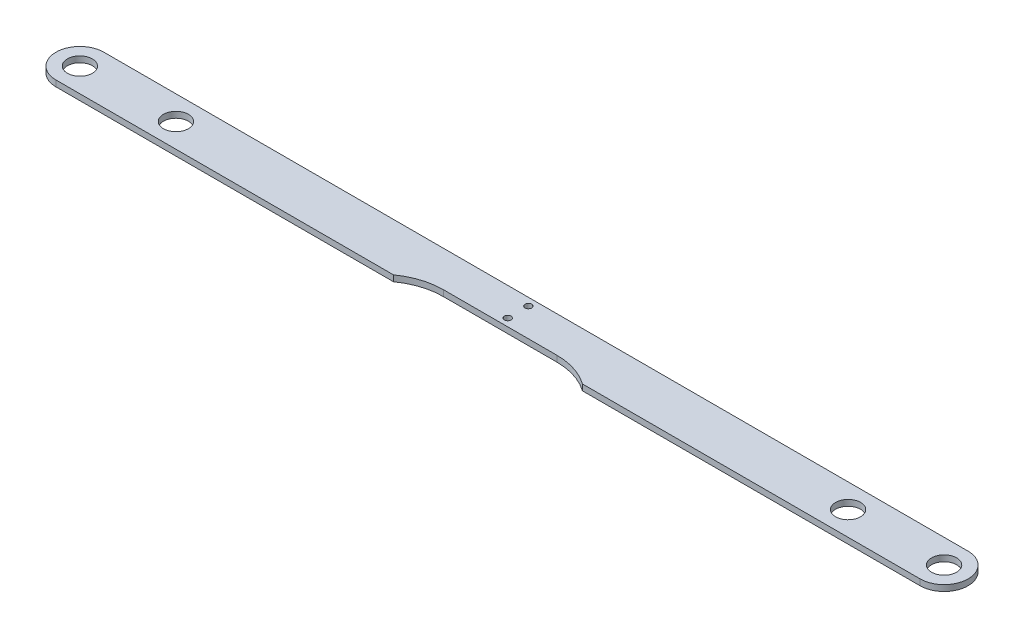
SolidWorks part; units mm, degrees
ref_plane "Front Plane" through (0, 0, 0) normal (0, 0, 1) x (1, 0, 0)
ref_plane "Top Plane" through (0, 0, 0) normal (0, 1, 0) x (1, 0, 0)
ref_plane "Right Plane" through (0, 0, 0) normal (1, 0, 0) x (0, 0, -1)
sketch "Sketch5" plane through (0, 0, 0) normal (0, 1, 0) x (1, 0, 0)
  line L0 (0, 2.75) -> (0, -2.75) construction
  line L1 (0, 4.75) -> (-114.3, 4.75)
  line L2 (-114.3, -7.95) -> (-114.3, 4.75) construction
  line L3 (0, 4.75) -> (0, -4.75)
  line L4 (-114.3, -1.6) -> (-88.9, -1.6) construction
  line L6 (-15, -4.75) -> (-15, -21.975) construction
  line L15 (-114.3, -7.95) -> (-25, -7.95)
  line L21 (-15, -4.75) -> (0, -4.75)
  circle A0 centre (-114.3, -1.6) radius 3.302
  circle A1 centre (0, 2.75) radius 0.889 construction
  circle A3 centre (0, -2.75) radius 0.889 construction
  arc A4 (-114.3, 4.75) -> (-114.3, -7.95) centre (-114.3, -1.6) ccw
  arc A8 (-15, -4.75) -> (-25, -7.95) centre (-15, -21.975) ccw
  circle A9 centre (-88.9, -1.6) radius 3.302
  point P11 (0, 0)
  dimension "D2" = 15
  dimension "D3" = 1.778
  dimension "D12" = 6.604
  dimension "D13" = 25.4
  dimension "D4" = 9.5
  dimension "D5" = 12.7
  dimension "D6" = 114.3
  dimension "D7" = 5.5
  dimension "D8" = 10
extrude "Boss-Extrude1" add sketch "Sketch5" along normal blind 1.5875
mirror "Mirror1" about plane through (0, 1.5875, -4.75) normal (-1, 0, 0) of "Boss-Extrude1"
sketch "Sketch6" plane through (0, 0, 0) normal (0, 1, 0) x (1, 0, 0)
  line L0 (0, 2.75) -> (0, -2.75) construction
  circle A0 centre (0, 2.75) radius 0.89
  circle A1 centre (0, -2.75) radius 0.89
  point P2 (0, 0)
  dimension "D2" = 1.78
  dimension "D1" = 5.5
extrude "Cut-Extrude2" cut sketch "Sketch6" along normal through all
